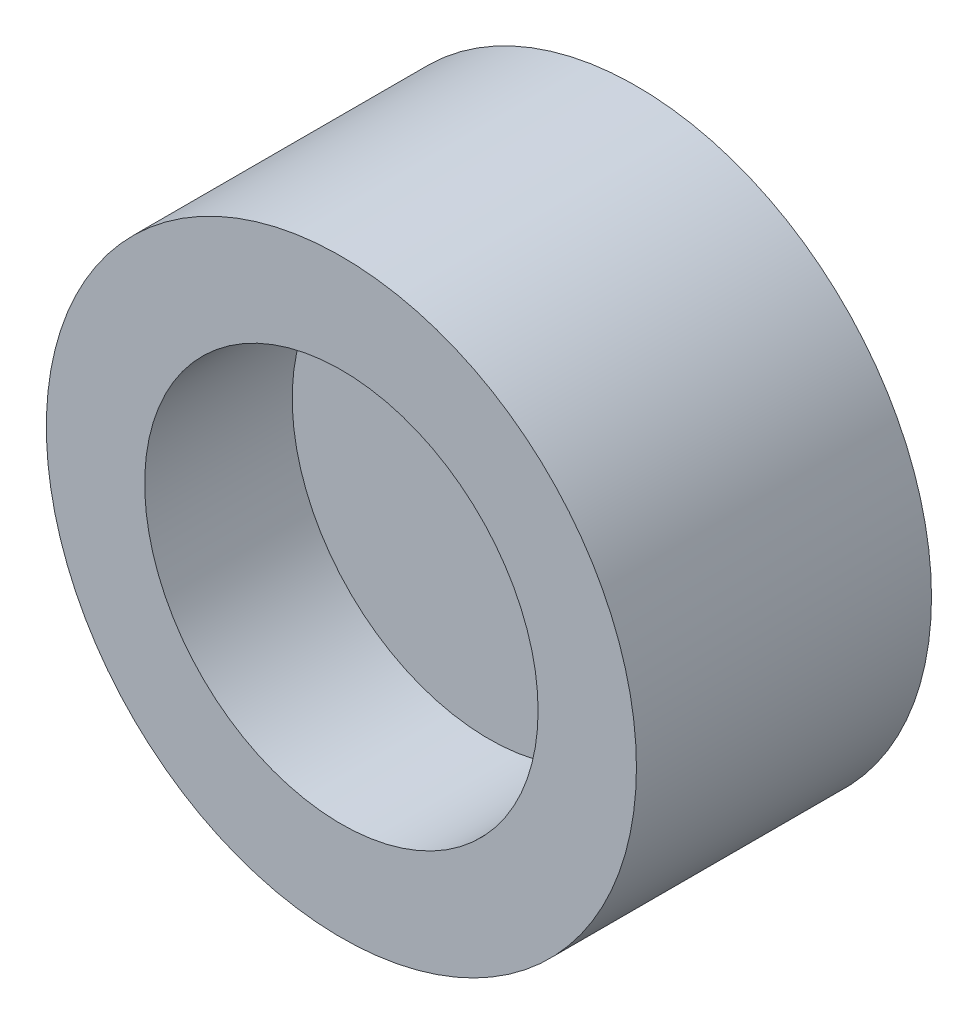
SolidWorks part; units mm, degrees
ref_plane "Front" through (0, 0, 0) normal (0, 0, 1) x (1, 0, 0)
ref_plane "Top" through (0, 0, 0) normal (0, 1, 0) x (1, 0, 0)
ref_plane "Right" through (0, 0, 0) normal (1, 0, 0) x (0, 0, -1)
sketch "Эскиз1" plane through (0, 0, 0) normal (0, 0, 1) x (1, 0, 0)
  circle A0 centre (0, 0) radius 3
extrude "Бобышка-Вытянуть1" add sketch "Эскиз1" along normal blind 3
sketch "Эскиз2" plane through (0, 0, 3) normal (0, 0, 1) x (1, 0, 0)
  circle A0 centre (0, 0) radius 2
extrude "Вырез-Вытянуть1" cut sketch "Эскиз2" against normal blind 1.5
